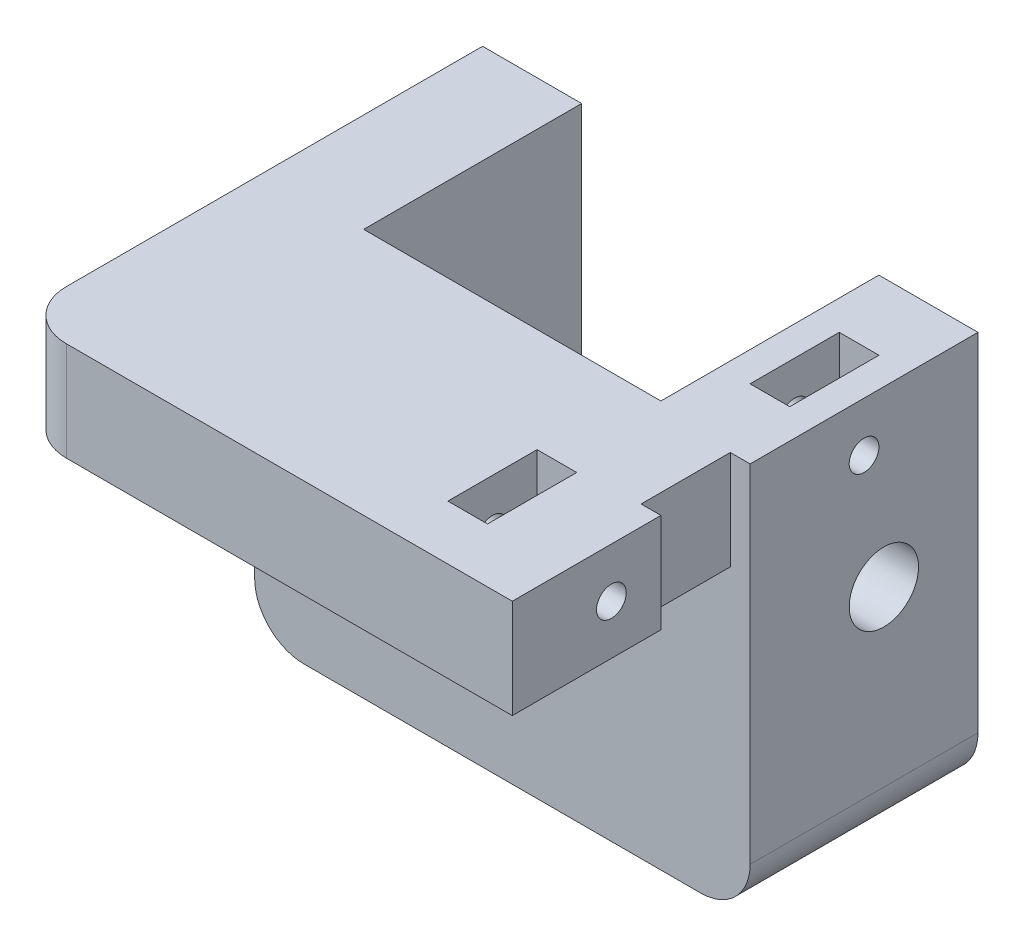
SolidWorks part; units mm, degrees
ref_plane "Front Plane" through (0, 0, 0) normal (0, 0, 1) x (1, 0, 0)
ref_plane "Top Plane" through (0, 0, 0) normal (0, 1, 0) x (1, 0, 0)
ref_plane "Right Plane" through (0, 0, 0) normal (1, 0, 0) x (0, 0, -1)
sketch "Sketch1" plane through (0, 0, 0) normal (0, 0, 1) x (1, 0, 0)
  line L0 (0, 30) -> (-10, 30)
  line L1 (0, 0) -> (30, 0)
  line L2 (0, 0) -> (0, 30)
  line L4 (30, 0) -> (30, 30)
  line L5 (-10, 30) -> (-10, -10)
  line L6 (-10, -10) -> (40, -10)
  line L7 (40, -10) -> (40, 30)
  line L8 (40, 30) -> (30, 30)
  dimension "D1" = 30
  dimension "D2" = 30
  dimension "D3" = 10
  dimension "D4" = 10
  dimension "D5" = 40
extrude "Boss-Extrude1" add sketch "Sketch1" along normal blind 22
sketch "Sketch3" plane through (0, 0, 22) normal (0, 0, 1) x (1, 0, 0)
  line L0 (0, 0) -> (0, 30) construction
  line L1 (-10, 30) -> (0, 30)
  line L2 (-10, 30) -> (-10, 20)
  line L3 (-10, 20) -> (0, 20)
  line L4 (0, 30) -> (0, 20)
  dimension "D1" = 10
extrude "Boss-Extrude2" add sketch "Sketch3" along normal blind 25
sketch "Sketch4" plane through (0, 0, 0) normal (1, 0, 0) x (0, 0, -1)
  line L1 (-22, 20) -> (-47, 20)
  line L2 (-22, 20) -> (-22, 30)
  line L3 (-22, 30) -> (-47, 30)
  line L4 (-47, 20) -> (-47, 30)
extrude "Boss-Extrude3" add sketch "Sketch4" along normal blind 40
sketch "Sketch5" plane through (0, 20, 0) normal (0, -1, 0) x (1, 0, 0)
  line L1 (40, 22) -> (38, 22)
  line L2 (40, 22) -> (40, 32)
  line L3 (40, 32) -> (38, 32)
  line L4 (38, 22) -> (38, 32)
  dimension "D1" = 10
  dimension "D2" = 2
extrude "Cut-Extrude4" cut sketch "Sketch5" against normal blind 40
sketch "Sketch6" plane through (0, 0, 22) normal (0, 0, 1) x (1, 0, 0)
  line L0 (-10, 20) -> (38, 20)
  line L1 (38, 20) -> (38, 30)
  line L2 (38, 30) -> (40, 30)
  line L3 (40, 30) -> (40, -10)
  line L4 (40, -10) -> (-10, -10)
  line L5 (-10, -10) -> (-10, 20)
extrude "Boss-Extrude4" add sketch "Sketch6" along normal blind 1
sketch "Sketch7" plane through (40, 0, 0) normal (1, 0, 0) x (0, 0, -1)
  circle A0 centre (-37, 25) radius 1.5
  circle A1 centre (-17, 25) radius 1.5
  dimension "D2" = 3
  dimension "D3" = 3
  dimension "D1" = 5
  dimension "D4" = 6
extrude "Cut-Extrude5" cut sketch "Sketch7" against normal blind 15
sketch "Sketch8" plane through (0, 30, 0) normal (0, 1, 0) x (1, 0, 0)
  line L0 (40, 0) -> (30, 0) construction
  line L1 (37, -12.5) -> (33, -12.5)
  line L2 (37, -12.5) -> (37, -21.5)
  line L3 (37, -21.5) -> (33, -21.5)
  line L4 (33, -12.5) -> (33, -21.5)
  line L6 (32, -32.5) -> (28, -32.5)
  line L7 (32, -32.5) -> (32, -41.5)
  line L8 (32, -41.5) -> (28, -41.5)
  line L9 (28, -32.5) -> (28, -41.5)
  point P4 (37, -17)
  point P6 (35, 0)
  point P9 (35, -12.5)
  point P14 (30, -41.5)
  dimension "D1" = 6
  dimension "D2" = 9
  dimension "D3" = 4
  dimension "D4" = 0
  dimension "D5" = 9
  dimension "D6" = 10
  dimension "D7" = 0.5
extrude "Cut-Extrude6" cut sketch "Sketch8" against normal blind 15
fillet "Fillet1" radius 5 1 edges at (40, -10, 11.5)
fillet "Fillet2" radius 5 1 edges at (-10, -10, 11.5)
fillet "Fillet3" radius 5 1 edges at (-10, 25, 47)
sketch "Sketch9" plane through (40, 0, 0) normal (1, 0, 0) x (0, 0, -1)
  line L0 (-23, -5) -> (-23, 30) construction
  circle A0 centre (-9.5, 12.5) radius 3.5
  dimension "D1" = 7
  dimension "D2" = 13.5
extrude "Cut-Extrude7" cut sketch "Sketch9" against normal blind 1000
sketch "Sketch10" plane through (0, 30, 0) normal (0, 1, 0) x (1, 0, 0)
  line L1 (33, -12.5) -> (37, -12.5)
  line L2 (33, -12.5) -> (33, -21.5)
  line L3 (33, -21.5) -> (37, -21.5)
  line L4 (37, -12.5) -> (37, -21.5)
extrude "Boss-Extrude5" add sketch "Sketch10" against normal blind 15
sketch "Sketch11" plane through (40, 0, 0) normal (1, 0, 0) x (0, 0, -1)
  circle A0 centre (-17, 25) radius 1.5
extrude "Boss-Extrude6" add sketch "Sketch11" against normal blind 10
sketch "Sketch12" plane through (40, 0, 0) normal (1, 0, 0) x (0, 0, -1)
  circle A0 centre (-11.5, 25) radius 1.5
  dimension "D2" = 3
  dimension "D1" = 5
extrude "Cut-Extrude8" cut sketch "Sketch12" against normal blind 19
sketch "Sketch13" plane through (0, 30, 0) normal (0, 1, 0) x (1, 0, 0)
  line L0 (40, -23) -> (40, 0) construction
  line L1 (37.0024, -16) -> (32.9976, -16)
  line L2 (37.0024, -16) -> (37.0024, -7)
  line L3 (37.0024, -7) -> (32.9976, -7)
  line L4 (32.9976, -16) -> (32.9976, -7)
  point P4 (35, -7)
  point P6 (37.0024, -11.5)
  point P9 (40, -11.5)
  dimension "D1" = 5
  dimension "D2" = 4.0048
  dimension "D3" = 9
  dimension "D4" = 0
extrude "Cut-Extrude9" cut sketch "Sketch13" against normal blind 10
